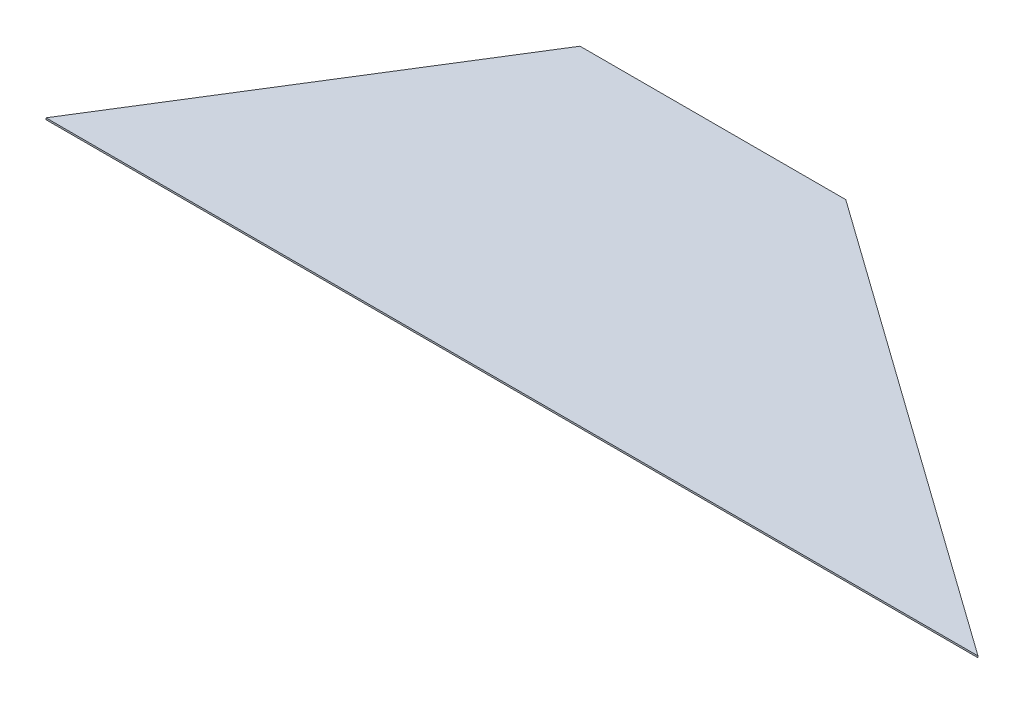
SolidWorks part; units mm, degrees
material "Hexcel AS4C (3000 Filaments)"
ref_plane "Front Plane" through (0, 0, 0) normal (0, 0, 1) x (1, 0, 0)
ref_plane "Top Plane" through (0, 0, 0) normal (0, 1, 0) x (1, 0, 0)
ref_plane "Right Plane" through (0, 0, 0) normal (1, 0, 0) x (0, 0, -1)
sketch "Sketch1" plane through (0, 0, 0) normal (0, 1, 0) x (1, 0, 0)
  line L0 (263.1775, -51.7166) -> (-162.748, -51.7166)
  line L1 (-162.748, -51.7166) -> (-69.0607, 98.6514)
  line L2 (-69.0607, 98.6514) -> (52.3812, 98.6514)
  line L3 (283.014, -58.0666) -> (-174.186, -58.0666) construction
  line L4 (54.414, 105.0014) -> (283.014, -58.0666) construction
  line L5 (-72.586, 105.0014) -> (54.414, 105.0014) construction
  line L6 (-174.186, -58.0666) -> (-72.586, 105.0014) construction
  line L7 (52.3812, 98.6514) -> (263.1775, -51.7166)
  dimension "D1" = 6.35
extrude "Boss-Extrude1" add sketch "Sketch1" along normal blind 0.762
